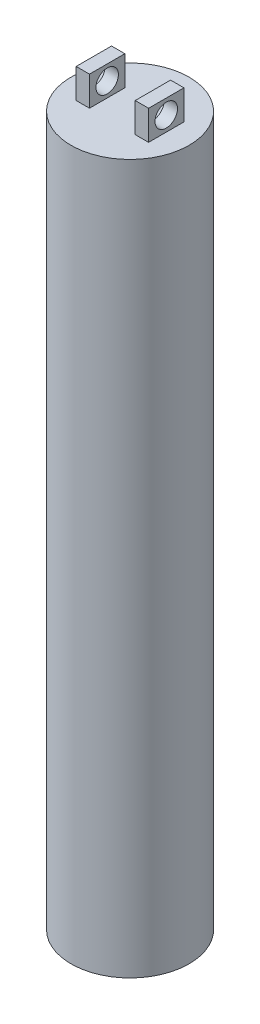
SolidWorks part; units mm, degrees
ref_plane "Front Plane" through (0, 0, 0) normal (0, 0, 1) x (1, 0, 0)
ref_plane "Top Plane" through (0, 0, 0) normal (0, 1, 0) x (1, 0, 0)
ref_plane "Right Plane" through (0, 0, 0) normal (1, 0, 0) x (0, 0, -1)
sketch "Sketch1" plane through (0, 0, 0) normal (0, 1, 0) x (1, 0, 0)
  circle A0 centre (0, 0) radius 25.4
  dimension "D1" = 50.8
extrude "Boss-Extrude1" add sketch "Sketch1" along normal blind 304.8
sketch "Sketch3" plane through (0, 304.8, 0) normal (0, 1, 0) x (1, 0, 0)
  line L0 (-9.8334, 7.6067) -> (9.8232, 7.6067)
  line L3 (-15.5666, -7.6067) -> (-9.8334, -7.6067)
  line L4 (9.8232, -7.6067) -> (15.5768, -7.6067)
  line L5 (9.8232, -7.6067) -> (9.8232, 7.6067)
  line L6 (9.8232, 7.6067) -> (15.5768, 7.6067)
  line L7 (15.5768, -7.6067) -> (15.5768, 7.6067)
  line L8 (9.8232, -7.6067) -> (15.5768, 7.6067) construction
  line L9 (9.8232, 7.6067) -> (15.5768, -7.6067) construction
  line L10 (-15.5666, -7.6067) -> (-15.5666, 7.6067)
  line L11 (-15.5666, 7.6067) -> (-9.8334, 7.6067)
  line L12 (-9.8334, -7.6067) -> (-9.8334, 7.6067)
  line L13 (-15.5666, -7.6067) -> (-9.8334, 7.6067) construction
  line L14 (-15.5666, 7.6067) -> (-9.8334, -7.6067) construction
  point P6 (12.7, 0)
  point P12 (-12.7, 0)
  dimension "D1" = 19.6566
extrude "Boss-Extrude2" add sketch "Sketch3" along normal blind 12.7 contours L4 L7 L6 L5 | L3 L12 L11 L10
sketch "Sketch4" plane through (15.5768, 0, 0) normal (1, 0, 0) x (0, 0, -1)
  line L0 (0, 317.5) -> (0, 304.8)
  line L1 (-7.6067, 317.5) -> (7.6067, 317.5) construction
  line L2 (-7.6067, 304.8) -> (7.6067, 304.8) construction
  circle A0 centre (0, 311.15) radius 4.826
sketch "Sketch5" plane through (0, 304.8, 0) normal (0, 1, 0) x (1, 0, 0)
  line L1 (-15.5666, 7.6067) -> (-9.8334, 7.6067)
  line L2 (-15.5666, 7.6067) -> (-15.5666, -7.6067)
  line L3 (-15.5666, -7.6067) -> (-9.8334, -7.6067)
  line L4 (-9.8334, 7.6067) -> (-9.8334, -7.6067)
  line L5 (9.8232, 7.6067) -> (15.5768, 7.6067)
  line L6 (9.8232, 7.6067) -> (9.8232, -7.6067)
  line L7 (9.8232, -7.6067) -> (15.5768, -7.6067)
  line L8 (15.5768, 7.6067) -> (15.5768, -7.6067)
extrude "Cut-Extrude2" cut sketch "Sketch4" against normal blind 62.738 contours L0 A0 | L0 A0
sketch "Sketch6" plane through (0, 0, 0) normal (0, -1, 0) x (1, 0, 0)
  line L0 (0, 0) -> (-25.4, 0)
  line L1 (0, 0) -> (25.4, 0)
  circle A0 centre (0, 0) radius 25.4 construction
  circle A1 centre (-12.7, 0) radius 4.7625
  circle A2 centre (12.7, 0) radius 4.7625
  dimension "D1" = 9.525
  dimension "D2" = 9.525
extrude "Cut-Extrude3" cut sketch "Sketch6" against normal blind 2.54 contours A1 | A2
